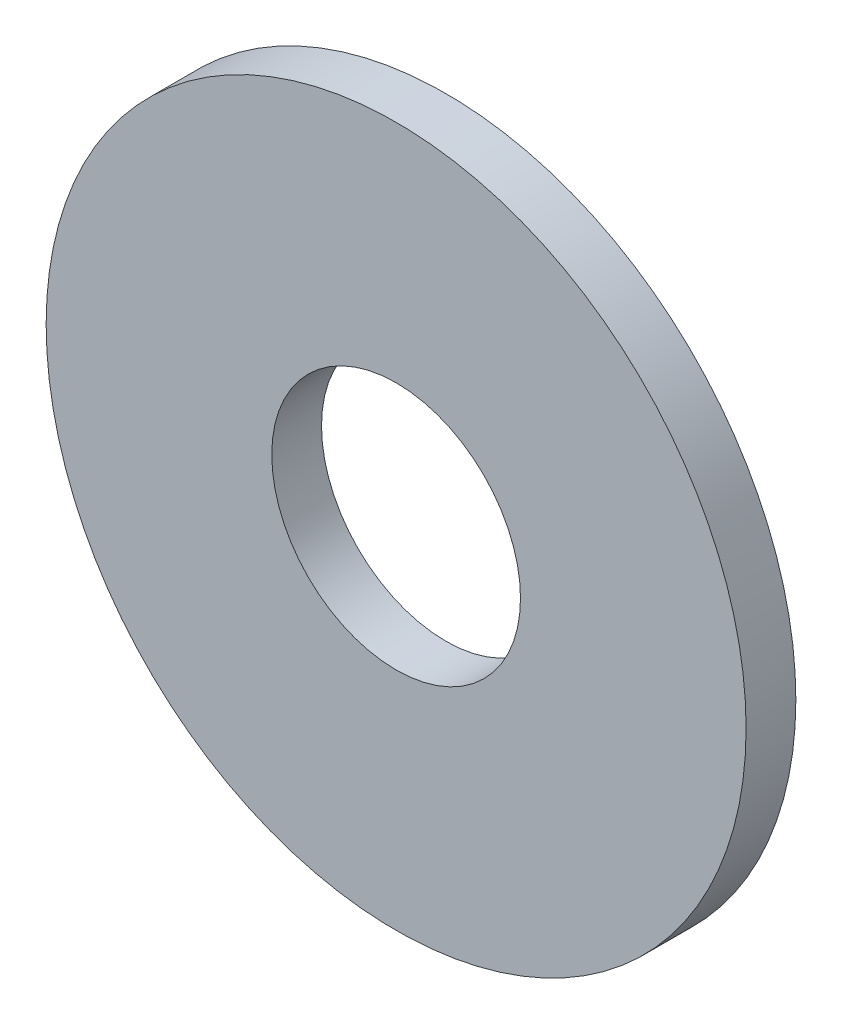
SolidWorks part; units mm, degrees
ref_plane "Front Plane" through (0, 0, 0) normal (0, 0, 1) x (1, 0, 0)
ref_plane "Top Plane" through (0, 0, 0) normal (0, 1, 0) x (1, 0, 0)
ref_plane "Right Plane" through (0, 0, 0) normal (1, 0, 0) x (0, 0, -1)
sketch "Sketch1" plane through (0, 0, 0) normal (0, 0, 1) x (1, 0, 0)
  circle A0 centre (0, 0) radius 17.8689
  circle A1 centre (0, 0) radius 6.35
extrude "Boss-Extrude1" add sketch "Sketch1" along normal blind 2.54
move or copy body "Body-Move/Copy1" [suppressed] bodies to move or copy 102
